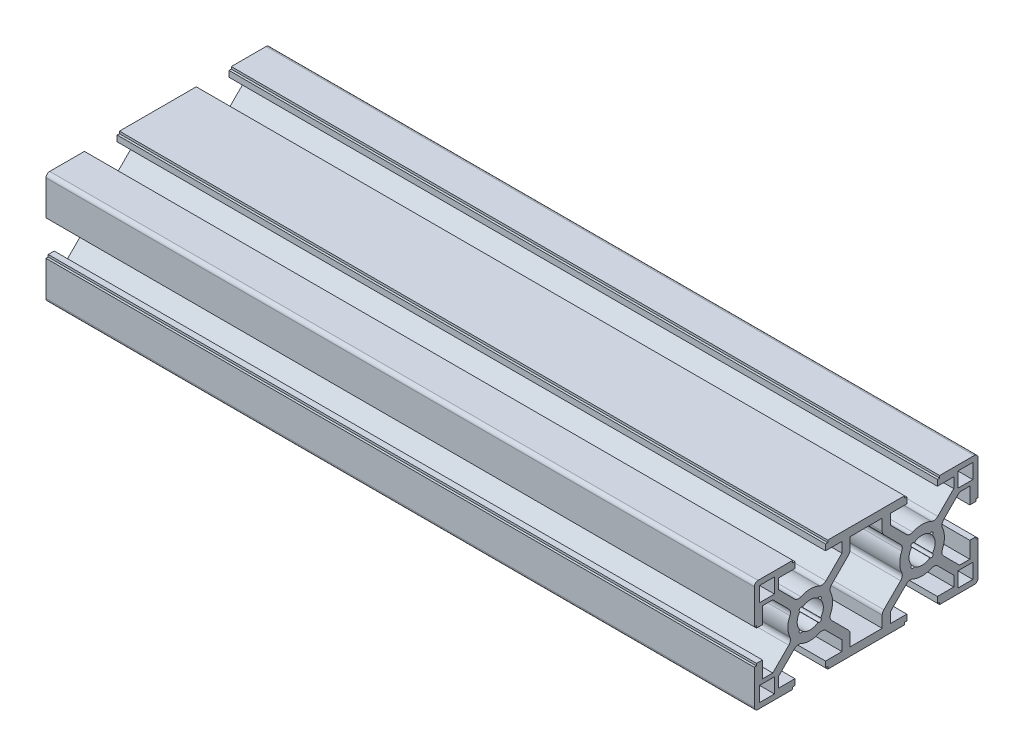
SolidWorks part; units mm, degrees
ref_plane "Front Plane" through (0, 0, 0) normal (0, 0, 1) x (1, 0, 0)
ref_plane "Top Plane" through (0, 0, 0) normal (0, 1, 0) x (1, 0, 0)
ref_plane "Right Plane" through (0, 0, 0) normal (1, 0, 0) x (0, 0, -1)
ref_plane "Plane1" through (-190, 0, 0) normal (-1, 0, 0) x (0, -1, 0)
sketch "Sketch1" plane through (-190, 0, 0) normal (-1, 0, 0) x (0, -1, 0)
  line L0 (-20.7523, 10.8034) -> (-25.0556, 6.5)
  line L1 (-25.0556, 6.5) -> (-27.8, 6.5)
  line L2 (-27.8, 6.5) -> (-27.8, 10.9)
  line L3 (-27.8, 10.9) -> (-29.4, 10.9)
  line L4 (-29.4, 10.9) -> (-29.4, 10.3)
  line L5 (-29.4, 10.3) -> (-30, 10.3)
  line L6 (-30, 10.3) -> (-30, 1)
  line L7 (-29, 0) -> (-19.7, 0)
  line L8 (-19.7, 0) -> (-19.7, 0.6)
  line L9 (-19.7, 0.6) -> (-19.1, 0.6)
  line L10 (-19.1, 0.6) -> (-19.1, 2.2)
  line L11 (-19.1, 2.2) -> (-23.5, 2.2)
  line L12 (-23.5, 2.2) -> (-23.5, 4.9444)
  line L13 (-23.5, 4.9444) -> (-19.1966, 9.2477)
  line L14 (-10.8034, 9.2477) -> (-6.5, 4.9444)
  line L15 (-6.5, 4.9444) -> (-6.5, 2.2)
  line L16 (-6.5, 2.2) -> (-10.9, 2.2)
  line L17 (-10.9, 2.2) -> (-10.9, 0.6)
  line L18 (-10.9, 0.6) -> (-10.3, 0.6)
  line L19 (-10.3, 0.6) -> (-10.3, 0)
  line L20 (-10.3, 0) -> (-1, 0)
  line L21 (0, 1) -> (0, 10.3)
  line L22 (0, 10.3) -> (-0.6, 10.3)
  line L23 (-0.6, 10.3) -> (-0.6, 10.9)
  line L24 (-0.6, 10.9) -> (-2.2, 10.9)
  line L25 (-2.2, 10.9) -> (-2.2, 6.5)
  line L26 (-2.2, 6.5) -> (-4.9444, 6.5)
  line L27 (-4.9444, 6.5) -> (-9.2477, 10.8034)
  line L28 (-9.2477, 19.1966) -> (-4.9444, 23.5)
  line L29 (-4.9444, 23.5) -> (-2.2, 23.5)
  line L30 (-2.2, 23.5) -> (-2.2, 19.1)
  line L31 (-2.2, 19.1) -> (-0.6, 19.1)
  line L32 (-0.6, 19.1) -> (-0.6, 19.7)
  line L33 (-0.6, 19.7) -> (0, 19.7)
  line L34 (0, 19.7) -> (0, 40.3)
  line L35 (0, 40.3) -> (-0.6, 40.3)
  line L36 (-0.6, 40.3) -> (-0.6, 40.9)
  line L37 (-0.6, 40.9) -> (-2.2, 40.9)
  line L38 (-2.2, 40.9) -> (-2.2, 36.5)
  line L39 (-2.2, 36.5) -> (-4.9444, 36.5)
  line L40 (-4.9444, 36.5) -> (-9.2477, 40.8034)
  line L41 (-9.2477, 49.1966) -> (-4.9444, 53.5)
  line L42 (-4.9444, 53.5) -> (-2.2, 53.5)
  line L43 (-2.2, 53.5) -> (-2.2, 49.1)
  line L44 (-2.2, 49.1) -> (-0.6, 49.1)
  line L45 (-0.6, 49.1) -> (-0.6, 49.7)
  line L46 (-0.6, 49.7) -> (0, 49.7)
  line L47 (0, 49.7) -> (0, 59)
  line L48 (-1, 60) -> (-10.3, 60)
  line L49 (-10.3, 60) -> (-10.3, 59.4)
  line L50 (-10.3, 59.4) -> (-10.9, 59.4)
  line L51 (-10.9, 59.4) -> (-10.9, 57.8)
  line L52 (-10.9, 57.8) -> (-6.5, 57.8)
  line L53 (-6.5, 57.8) -> (-6.5, 55.0556)
  line L54 (-6.5, 55.0556) -> (-10.8034, 50.7523)
  line L55 (-19.1966, 50.7523) -> (-23.5, 55.0556)
  line L56 (-23.5, 55.0556) -> (-23.5, 57.8)
  line L57 (-23.5, 57.8) -> (-19.1, 57.8)
  line L58 (-19.1, 57.8) -> (-19.1, 59.4)
  line L59 (-19.1, 59.4) -> (-19.7, 59.4)
  line L60 (-19.7, 59.4) -> (-19.7, 60)
  line L61 (-19.7, 60) -> (-29, 60)
  line L62 (-30, 59) -> (-30, 49.7)
  line L63 (-30, 49.7) -> (-29.4, 49.7)
  line L64 (-29.4, 49.7) -> (-29.4, 49.1)
  line L65 (-29.4, 49.1) -> (-27.8, 49.1)
  line L66 (-27.8, 49.1) -> (-27.8, 53.5)
  line L67 (-27.8, 53.5) -> (-25.0556, 53.5)
  line L68 (-25.0556, 53.5) -> (-20.7523, 49.1966)
  line L69 (-20.7523, 40.8034) -> (-25.0556, 36.5)
  line L70 (-25.0556, 36.5) -> (-27.8, 36.5)
  line L71 (-27.8, 36.5) -> (-27.8, 40.9)
  line L72 (-27.8, 40.9) -> (-29.4, 40.9)
  line L73 (-29.4, 40.9) -> (-29.4, 40.3)
  line L74 (-29.4, 40.3) -> (-30, 40.3)
  line L75 (-30, 40.3) -> (-30, 19.7)
  line L76 (-30, 19.7) -> (-29.4, 19.7)
  line L77 (-29.4, 19.7) -> (-29.4, 19.1)
  line L78 (-29.4, 19.1) -> (-27.8, 19.1)
  line L79 (-27.8, 19.1) -> (-27.8, 23.5)
  line L80 (-27.8, 23.5) -> (-25.0556, 23.5)
  line L81 (-25.0556, 23.5) -> (-20.7523, 19.1966)
  line L82 (-28.6, 54.6) -> (-28.6, 58.6)
  line L83 (-28.6, 58.6) -> (-24.6, 58.6)
  line L84 (-24.6, 58.6) -> (-24.6, 54.6)
  line L85 (-24.6, 54.6) -> (-28.6, 54.6)
  line L86 (-1.4, 54.6) -> (-5.4, 54.6)
  line L87 (-5.4, 54.6) -> (-5.4, 58.6)
  line L88 (-5.4, 58.6) -> (-1.4, 58.6)
  line L89 (-1.4, 58.6) -> (-1.4, 54.6)
  line L90 (-28.6, 5.4) -> (-24.6, 5.4)
  line L91 (-24.6, 5.4) -> (-24.6, 1.4)
  line L92 (-24.6, 1.4) -> (-28.6, 1.4)
  line L93 (-28.6, 1.4) -> (-28.6, 5.4)
  line L94 (-1.4, 5.4) -> (-1.4, 1.4)
  line L95 (-1.4, 1.4) -> (-5.4, 1.4)
  line L96 (-5.4, 1.4) -> (-5.4, 5.4)
  line L97 (-5.4, 5.4) -> (-1.4, 5.4)
  line L98 (-10.8034, 39.2477) -> (-6.295, 34.7393)
  line L99 (-5.2343, 34.3) -> (-2.2, 34.3)
  line L100 (-2.2, 34.3) -> (-2.2, 25.7)
  line L101 (-2.2, 25.7) -> (-5.2343, 25.7)
  line L102 (-6.295, 25.2607) -> (-10.8034, 20.7523)
  line L103 (-19.1966, 20.7523) -> (-23.705, 25.2607)
  line L104 (-24.7657, 25.7) -> (-27.8, 25.7)
  line L105 (-27.8, 25.7) -> (-27.8, 34.3)
  line L106 (-27.8, 34.3) -> (-24.7657, 34.3)
  line L107 (-23.705, 34.7393) -> (-19.1966, 39.2477)
  arc A0 (-20.7523, 19.1966) -> (-20.4503, 17.5088) centre (-21.8129, 18.136) cw
  arc A1 (-20.4503, 17.5088) -> (-20.4503, 12.4912) centre (-15, 15) ccw
  arc A2 (-20.4503, 12.4912) -> (-20.7523, 10.8034) centre (-21.8129, 11.864) cw
  arc A3 (-30, 1) -> (-29, 0) centre (-29, 1) ccw
  arc A4 (-19.1966, 9.2477) -> (-17.5088, 9.5497) centre (-18.136, 8.1871) cw
  arc A5 (-17.5088, 9.5497) -> (-12.4912, 9.5497) centre (-15, 15) ccw
  arc A6 (-12.4912, 9.5497) -> (-10.8034, 9.2477) centre (-11.864, 8.1871) cw
  arc A7 (-1, 0) -> (0, 1) centre (-1, 1) ccw
  arc A8 (-9.2477, 10.8034) -> (-9.5497, 12.4912) centre (-8.1871, 11.864) cw
  arc A9 (-9.5497, 12.4912) -> (-9.5497, 17.5088) centre (-15, 15) ccw
  arc A10 (-9.5497, 17.5088) -> (-9.2477, 19.1966) centre (-8.1871, 18.136) cw
  arc A11 (-9.2477, 40.8034) -> (-9.5497, 42.4912) centre (-8.1871, 41.864) cw
  arc A12 (-9.5497, 42.4912) -> (-9.5497, 47.5088) centre (-15, 45) ccw
  arc A13 (-9.5497, 47.5088) -> (-9.2477, 49.1966) centre (-8.1871, 48.136) cw
  arc A14 (0, 59) -> (-1, 60) centre (-1, 59) ccw
  arc A15 (-10.8034, 50.7523) -> (-12.4912, 50.4503) centre (-11.864, 51.8129) cw
  arc A16 (-12.4912, 50.4503) -> (-17.5088, 50.4503) centre (-15, 45) ccw
  arc A17 (-17.5088, 50.4503) -> (-19.1966, 50.7523) centre (-18.136, 51.8129) cw
  arc A18 (-29, 60) -> (-30, 59) centre (-29, 59) ccw
  arc A19 (-20.7523, 49.1966) -> (-20.4503, 47.5088) centre (-21.8129, 48.136) cw
  arc A20 (-20.4503, 47.5088) -> (-20.4503, 42.4912) centre (-15, 45) ccw
  arc A21 (-20.4503, 42.4912) -> (-20.7523, 40.8034) centre (-21.8129, 41.864) cw
  arc A22 (-17.8023, 47.097) -> (-17.097, 47.8023) centre (-17.4749, 47.4749) cw
  arc A23 (-17.097, 47.8023) -> (-12.903, 47.8023) centre (-15, 45) cw
  arc A24 (-12.903, 47.8023) -> (-12.1977, 47.097) centre (-12.5251, 47.4749) cw
  arc A25 (-12.1977, 47.097) -> (-12.1977, 42.903) centre (-15, 45) cw
  arc A26 (-12.1977, 42.903) -> (-12.903, 42.1977) centre (-12.5251, 42.5251) cw
  arc A27 (-12.903, 42.1977) -> (-17.097, 42.1977) centre (-15, 45) cw
  arc A28 (-17.097, 42.1977) -> (-17.8023, 42.903) centre (-17.4749, 42.5251) cw
  arc A29 (-17.8023, 42.903) -> (-17.8023, 47.097) centre (-15, 45) cw
  arc A30 (-12.903, 12.1977) -> (-17.097, 12.1977) centre (-15, 15) cw
  arc A31 (-17.097, 12.1977) -> (-17.8023, 12.903) centre (-17.4749, 12.5251) cw
  arc A32 (-17.8023, 12.903) -> (-17.8023, 17.097) centre (-15, 15) cw
  arc A33 (-17.8023, 17.097) -> (-17.097, 17.8023) centre (-17.4749, 17.4749) cw
  arc A34 (-17.097, 17.8023) -> (-12.903, 17.8023) centre (-15, 15) cw
  arc A35 (-12.903, 17.8023) -> (-12.1977, 17.097) centre (-12.5251, 17.4749) cw
  arc A36 (-12.1977, 17.097) -> (-12.1977, 12.903) centre (-15, 15) cw
  arc A37 (-12.1977, 12.903) -> (-12.903, 12.1977) centre (-12.5251, 12.5251) cw
  arc A38 (-6.295, 34.7393) -> (-5.2343, 34.3) centre (-5.2343, 35.8) ccw
  arc A39 (-5.2343, 25.7) -> (-6.295, 25.2607) centre (-5.2343, 24.2) ccw
  arc A40 (-10.8034, 20.7523) -> (-12.4912, 20.4503) centre (-11.864, 21.8129) cw
  arc A41 (-12.4912, 20.4503) -> (-17.5088, 20.4503) centre (-15, 15) ccw
  arc A42 (-17.5088, 20.4503) -> (-19.1966, 20.7523) centre (-18.136, 21.8129) cw
  arc A43 (-23.705, 25.2607) -> (-24.7657, 25.7) centre (-24.7657, 24.2) ccw
  arc A44 (-24.7657, 34.3) -> (-23.705, 34.7393) centre (-24.7657, 35.8) ccw
  arc A45 (-19.1966, 39.2477) -> (-17.5088, 39.5497) centre (-18.136, 38.1871) cw
  arc A46 (-17.5088, 39.5497) -> (-12.4912, 39.5497) centre (-15, 45) ccw
  arc A47 (-12.4912, 39.5497) -> (-10.8034, 39.2477) centre (-11.864, 38.1871) cw
extrude "Boss-Extrude1" add sketch "Sketch1" against normal blind 190
